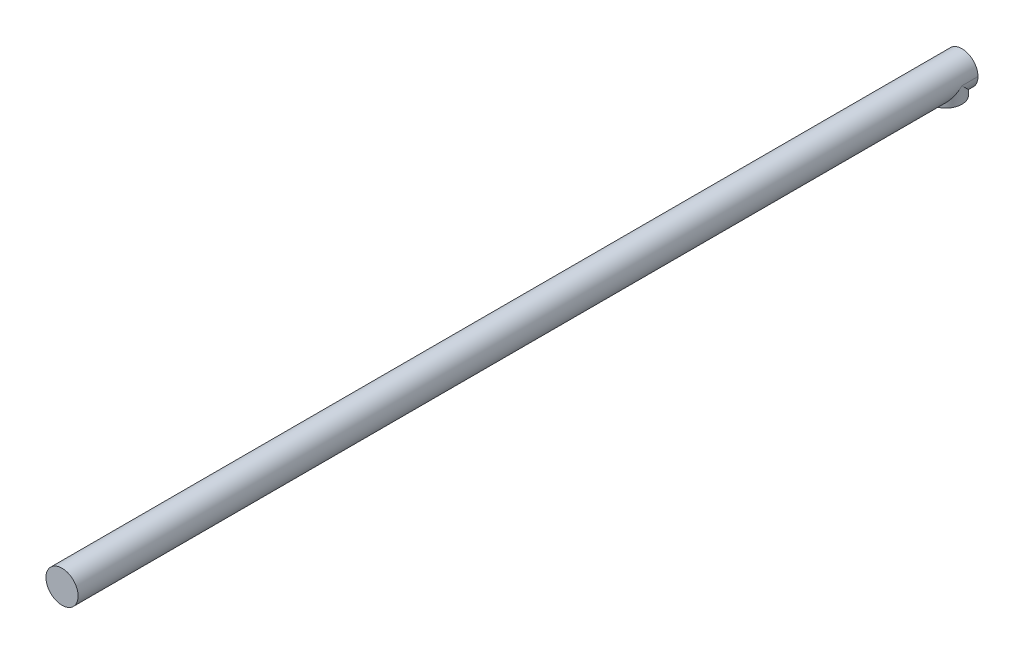
SolidWorks part; units mm, degrees
material "사용자정의 플라스틱"
ref_plane "정면" through (0, 0, 0) normal (0, 0, 1) x (1, 0, 0)
ref_plane "윗면" through (0, 0, 0) normal (0, 1, 0) x (1, 0, 0)
ref_plane "우측면" through (0, 0, 0) normal (1, 0, 0) x (0, 0, -1)
sketch "스케치1" plane through (0, 0, 0) normal (0, 0, 1) x (1, 0, 0)
  circle A0 centre (0, 0) radius 2.5
extrude "보스-돌출1" add sketch "스케치1" along normal blind 140
sketch "스케치2" plane through (0, 0, 0) normal (0, 1, 0) x (1, 0, 0)
  circle A0 centre (0, -2.5) radius 2.5
  dimension "D1" = 2.5
extrude "보스-돌출2" add sketch "스케치2" against normal blind 2.5
sketch "스케치3" plane through (0, 0, 0) normal (0, 1, 0) x (1, 0, 0)
  point P0 (0, -2.5)
